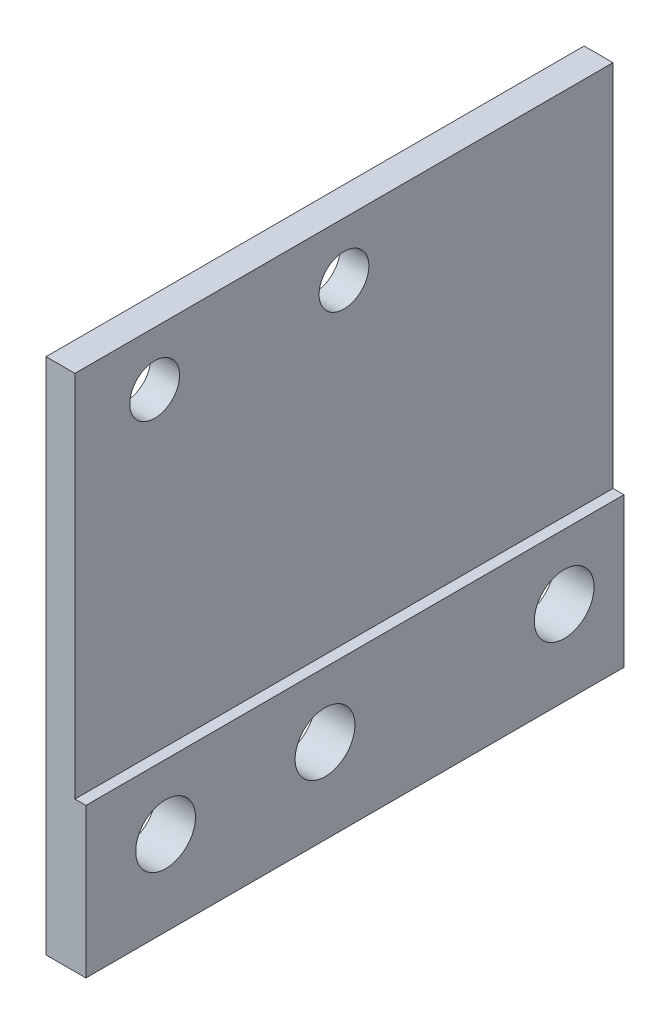
SolidWorks part; units mm, degrees
material "Aluminum"
ref_plane "Front Plane" through (0, 0, 0) normal (0, 0, 1) x (1, 0, 0)
ref_plane "Top Plane" through (0, 0, 0) normal (0, 1, 0) x (1, 0, 0)
ref_plane "Right Plane" through (0, 0, 0) normal (1, 0, 0) x (0, 0, -1)
sketch "Sketch1" plane through (0, 0, 0) normal (0, 0, 1) x (1, 0, 0)
  line L1 (0, 0) -> (2, 0)
  line L2 (0, 0) -> (0, 7.5)
  line L3 (1.45, 7.5) -> (2, 7.5)
  line L4 (2, 0) -> (2, 7.5)
  line L6 (0, 7.5) -> (0, 26)
  line L7 (0, 26) -> (1.45, 26)
  line L8 (1.45, 7.5) -> (1.45, 26)
  dimension "D1" = 2
  dimension "D2" = 1.45
  dimension "D3" = 7.5
  dimension "D4" = 18.5
extrude "Boss-Extrude1" add sketch "Sketch1" along normal blind 22 and the other way blind 5
hole_wizard "Tap Drill for M3x0.5 Tap1" positions "Sketch6" profile "Sketch4" hole size "M3x0.5" standard "ANSI Metric" end condition through all
sketch "Sketch6" plane through (2, 0, 0) normal (1, 0, 0) x (0, 0, -1)
  line L3 (-22, 7.5) -> (-22, 26) construction
  point P0 (-10, 4.25)
  point P3 (-18, 4.25)
  point P21 (2, 4.25)
  dimension "D1" = 12
  dimension "D2" = 8
  dimension "D3" = 12
sketch "Sketch4" plane through (2, 4.25, 10) normal (0, 1, 0) x (0, 0, -1)
  line L0 (0, 0) -> (0, 2)
  line L1 (0, 2) -> (1.5, 2)
  line L2 (1.5, 2) -> (1.5, 0)
  line L5 (1.5, 0) -> (0, 0)
  line L11 (0, -6.35) -> (0, 107.95) construction
  dimension "Thru Hole Dia." = 3
  dimension "Thru Hole Depth" = 2
hole_wizard "Tap Drill for M2.5x0.45 Tap1" positions "Sketch8" profile "Sketch7" hole size "M2.5x0.45" standard "ANSI Metric" end condition through all
sketch "Sketch8" plane through (1.45, 0, 0) normal (1, 0, 0) x (0, 0, -1)
  point P0 (-18, 23.2972)
  point P2 (-8.5, 23.2972)
sketch "Sketch7" plane through (1.45, 23.2972, 18) normal (0, 1, 0) x (0, 0, -1)
  line L0 (0, 0) -> (0, 1.45)
  line L1 (0, 1.45) -> (1.25, 1.45)
  line L2 (1.25, 1.45) -> (1.25, 0)
  line L5 (1.25, 0) -> (0, 0)
  line L11 (0, -6.35) -> (0, 107.95) construction
  dimension "Thru Hole Dia." = 2.5
  dimension "Thru Hole Depth" = 1.45
